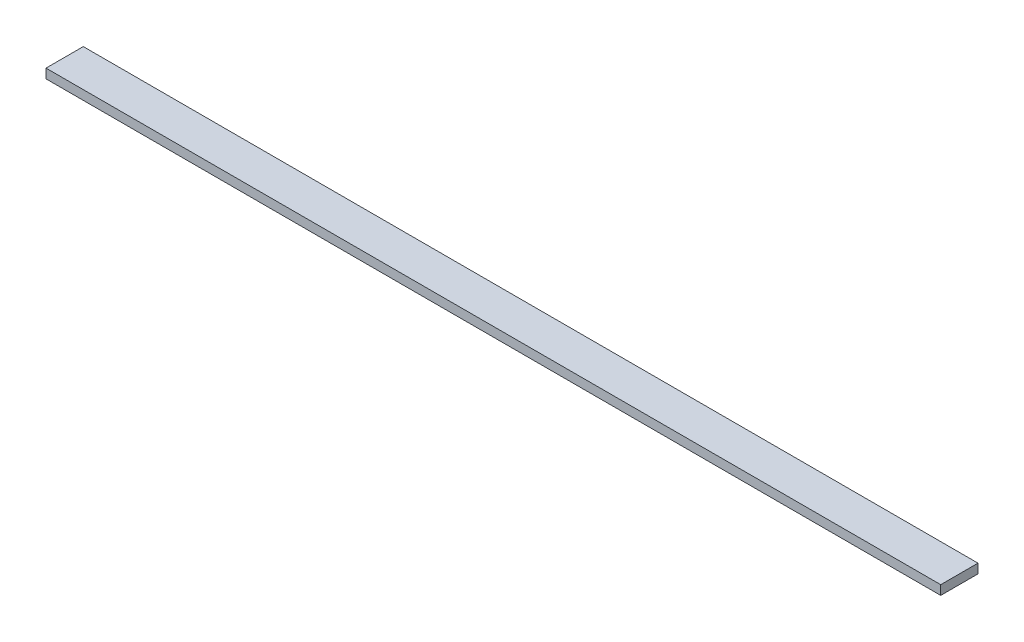
SolidWorks part; units mm, degrees
material "Polyurethane Foam Flexible"
ref_plane "Front Plane" through (0, 0, 0) normal (0, 0, 1) x (1, 0, 0)
ref_plane "Top Plane" through (0, 0, 0) normal (0, 1, 0) x (1, 0, 0)
ref_plane "Right Plane" through (0, 0, 0) normal (1, 0, 0) x (0, 0, -1)
sketch "Sketch1" plane through (0, 0, 0) normal (0, 1, 0) x (1, 0, 0)
  line L1 (-152.4, -6.35) -> (152.4, -6.35)
  line L2 (-152.4, -6.35) -> (-152.4, 6.35)
  line L3 (-152.4, 6.35) -> (152.4, 6.35)
  line L4 (152.4, -6.35) -> (152.4, 6.35)
  line L5 (-152.4, -6.35) -> (152.4, 6.35) construction
  line L6 (-152.4, 6.35) -> (152.4, -6.35) construction
  point P0 (0, 0)
  dimension "D1" = 12.7
  dimension "D2" = 304.8
extrude "Boss-Extrude1" add sketch "Sketch1" along normal blind 3.175
